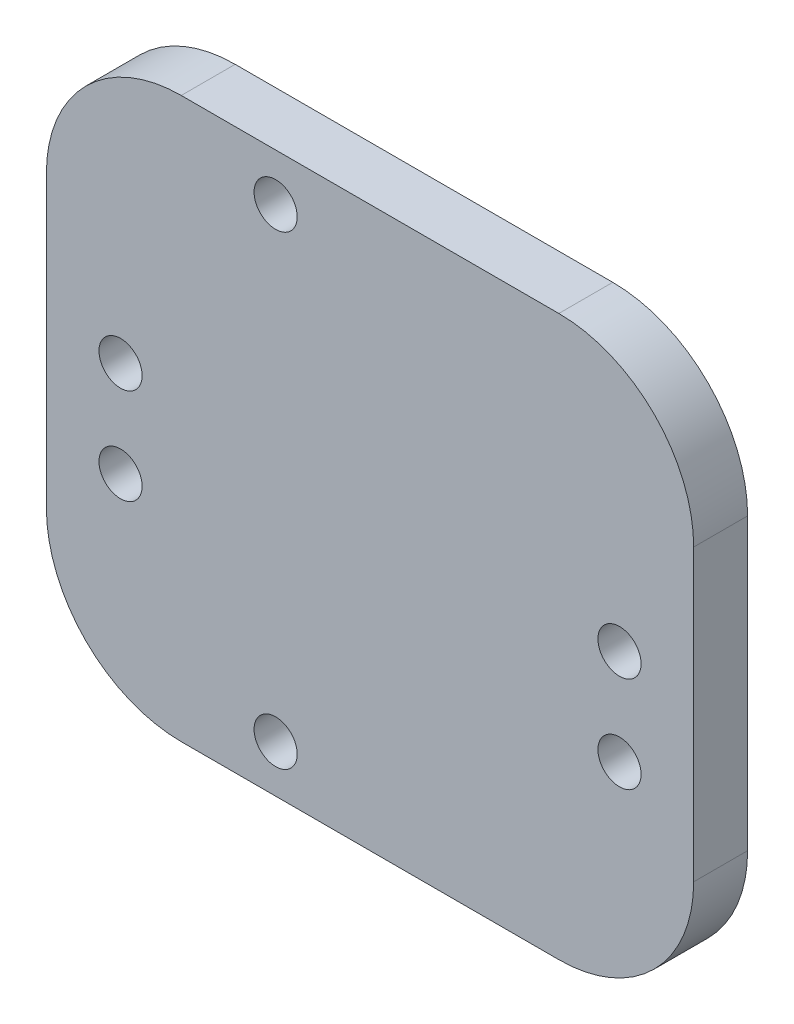
SolidWorks part; units mm, degrees
ref_plane "Front Plane" through (0, 0, 0) normal (0, 0, 1) x (1, 0, 0)
ref_plane "Top Plane" through (0, 0, 0) normal (0, 1, 0) x (1, 0, 0)
ref_plane "Right Plane" through (0, 0, 0) normal (1, 0, 0) x (0, 0, -1)
sketch "Sketch1" plane through (0, 0, 0) normal (0, 0, 1) x (1, 0, 0)
  line L1 (-14, 20.75) -> (14, 20.75)
  line L2 (-24, 10.75) -> (-24, -10.75)
  line L3 (-14, -20.75) -> (14, -20.75)
  line L4 (24, 10.75) -> (24, -10.75)
  line L5 (-24, 20.75) -> (24, -20.75) construction
  line L6 (-24, -20.75) -> (24, 20.75) construction
  arc A0 (14, -20.75) -> (24, -10.75) centre (14, -10.75) ccw
  arc A1 (14, 20.75) -> (24, 10.75) centre (14, 10.75) cw
  arc A2 (-24, -10.75) -> (-14, -20.75) centre (-14, -10.75) ccw
  arc A3 (-14, 20.75) -> (-24, 10.75) centre (-14, 10.75) ccw
  point P0 (0, 0)
  dimension "D1" = 10
  dimension "D2" = 28
  dimension "D3" = 21.5
extrude "Boss-Extrude1" add sketch "Sketch1" along normal blind 4
sketch "Sketch2" plane through (0, 0, 0) normal (0, 0, 1) x (1, 0, 0)
  line L0 (80.6323, 0) -> (-95.2428, 0) construction
  line L6 (18.5, -5.8) -> (-18.5, -5.8) construction
  line L7 (18.5, -5.8) -> (18.5, 1.3) construction
  line L8 (18.5, 1.3) -> (-18.5, 1.3) construction
  line L9 (-18.5, -5.8) -> (-18.5, 1.3) construction
  line L10 (18.5, -5.8) -> (-18.5, 1.3) construction
  line L11 (18.5, 1.3) -> (-18.5, -5.8) construction
  circle A0 centre (-7, 17.25) radius 1.6
  circle A2 centre (-7, 17.25) radius 3
  circle A3 centre (-7, -17.25) radius 3
  circle A4 centre (-7, -17.25) radius 1.6
  circle A5 centre (-18.5, -5.8) radius 1.6
  circle A6 centre (-18.5, 1.3) radius 1.6
  circle A7 centre (18.5, -5.8) radius 1.6
  circle A8 centre (18.5, 1.3) radius 1.6
  point P9 (0, -2.25)
  point P18 (0, 0)
  dimension "D1" = 3.2
  dimension "D3" = 6
  dimension "D8" = 3.2
  dimension "D2" = 17.25
  dimension "D4" = 37
  dimension "D5" = 7.1
  dimension "D6" = 2.25
  dimension "D7" = 7
extrude "Cut-Extrude1" cut sketch "Sketch2" along normal up to next contours A4 | A0 | A7 | A8 | A5 | A6
equation "\"width\"=28"
equation "\"D2@Sketch1\"=\"width\""
equation "\"length\"=21.5"
equation "\"D3@Sketch1\"=\"length\""
